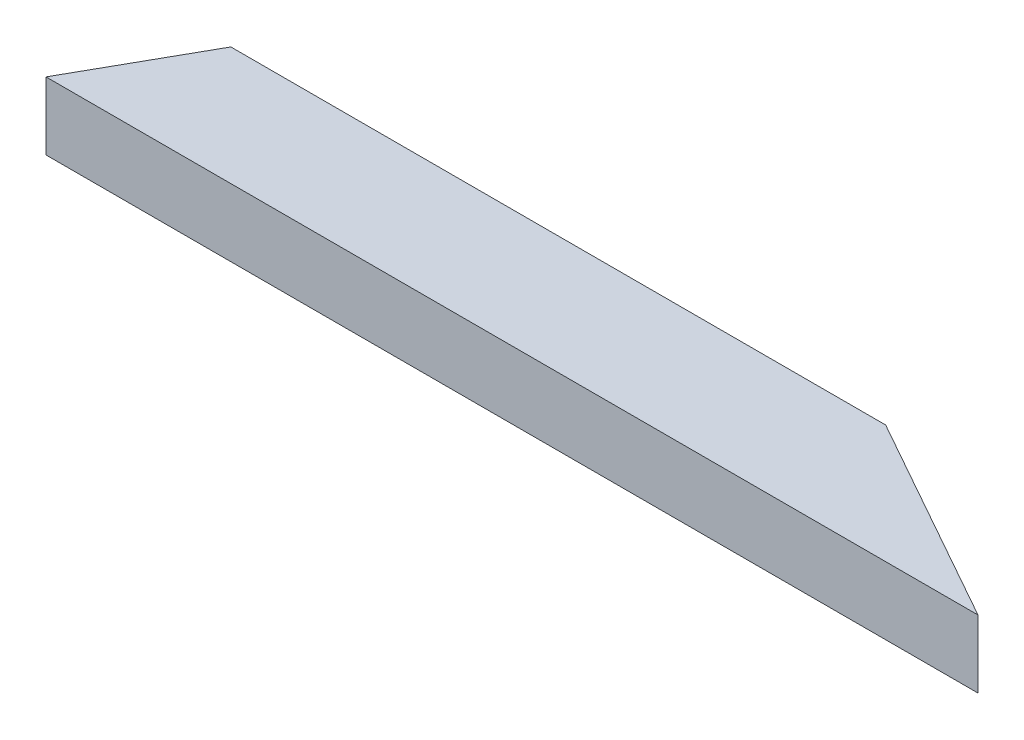
SolidWorks part; units mm, degrees
material "Pine"
ref_plane "Front Plane" through (0, 0, 0) normal (0, 0, 1) x (1, 0, 0)
ref_plane "Top Plane" through (0, 0, 0) normal (0, 1, 0) x (1, 0, 0)
ref_plane "Right Plane" through (0, 0, 0) normal (1, 0, 0) x (0, 0, -1)
sketch "Sketch1" plane through (0, 0, 0) normal (0, 1, 0) x (1, 0, 0)
  line L0 (0, 0) -> (700, 0)
  line L1 (700, 0) -> (541.7428, 88.9)
  line L2 (541.7428, 88.9) -> (49.939, 88.9)
  line L3 (49.939, 88.9) -> (0, 0)
  line L4 (350, 0) -> (350, 88.9) construction
  line L5 (0, 0) -> (167.9056, 298.9007) construction
  line L6 (167.9056, 298.9007) -> (700, 0) construction
  dimension "D1" = 88.9
  dimension "D2" = 700
  dimension "D3" = 491.8038
extrude "Boss-Extrude1" add sketch "Sketch1" along normal blind 50.8
